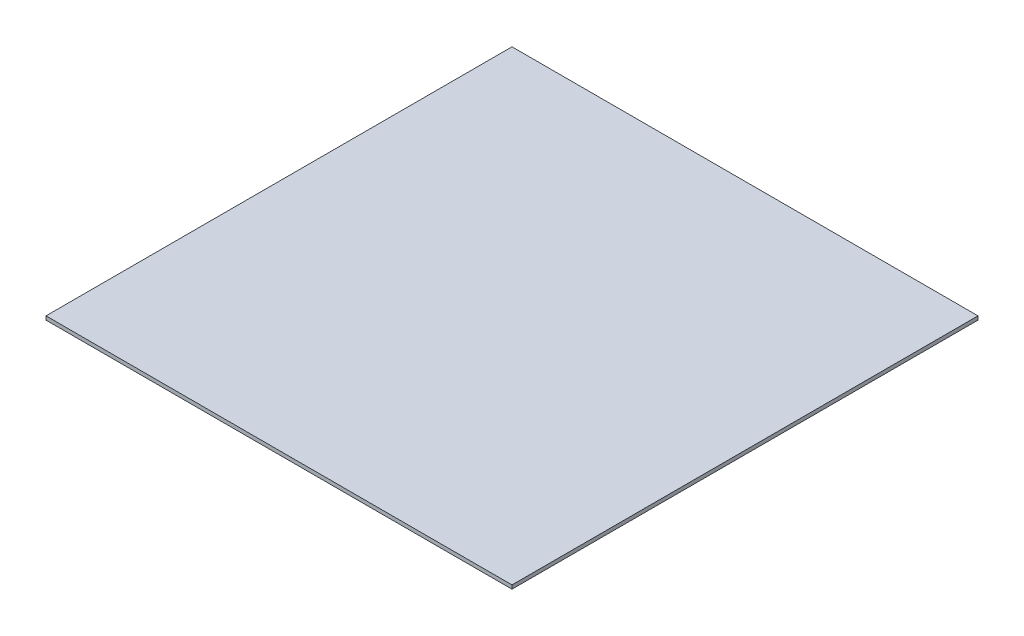
SolidWorks part; units mm, degrees
material "AISI 1020 Steel, Cold Rolled"
ref_plane "Front Plane" through (0, 0, 0) normal (0, 0, 1) x (1, 0, 0)
ref_plane "Top Plane" through (0, 0, 0) normal (0, 1, 0) x (1, 0, 0)
ref_plane "Right Plane" through (0, 0, 0) normal (1, 0, 0) x (0, 0, -1)
sketch "Sketch1" plane through (0, 0, 0) normal (0, 1, 0) x (1, 0, 0)
  line L1 (0, 0) -> (50, 0)
  line L2 (0, 0) -> (0, 50)
  line L3 (0, 50) -> (50, 50)
  line L4 (50, 0) -> (50, 50)
  dimension "D1" = 50
  dimension "D2" = 50
extrude "Boss-Extrude1" add sketch "Sketch1" along normal blind 0.4
